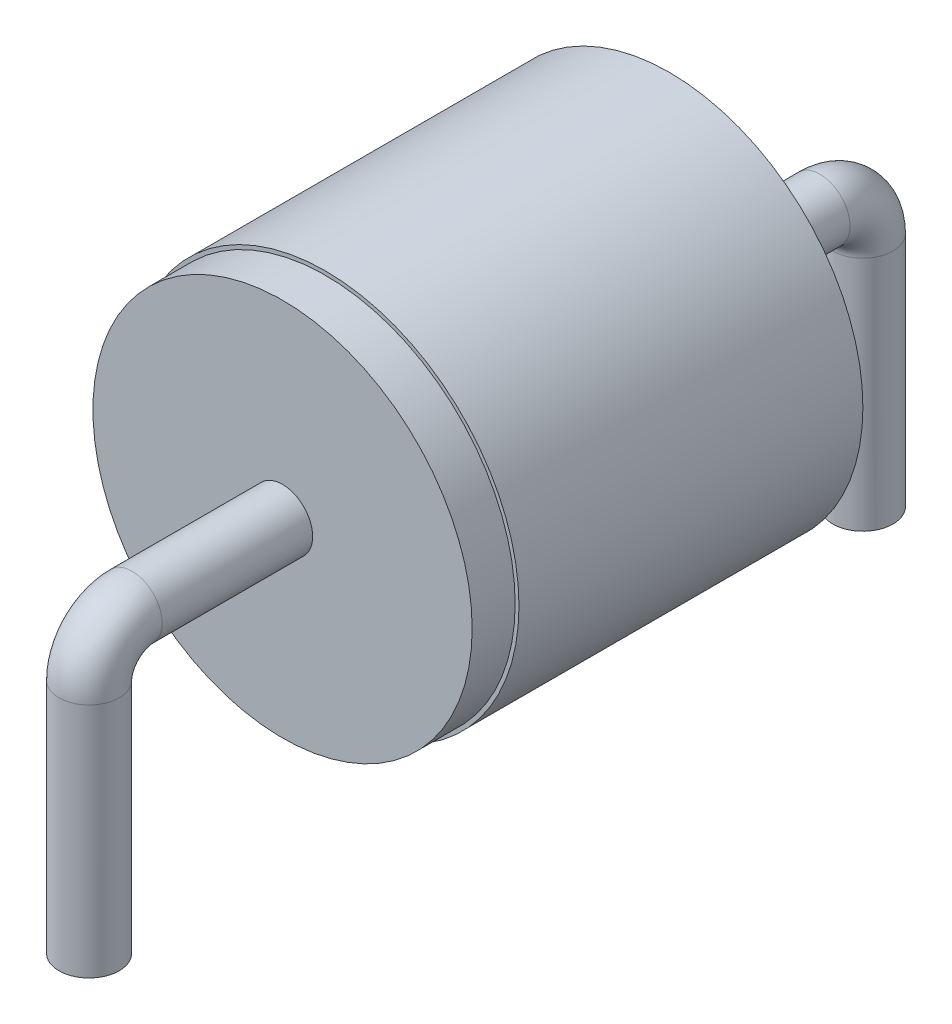
SolidWorks part; units mm, degrees
ref_plane "Спереди" through (0, 0, 0) normal (0, 0, 1) x (1, 0, 0)
ref_plane "Сверху" through (0, 0, 0) normal (0, 1, 0) x (1, 0, 0)
ref_plane "Справа" through (0, 0, 0) normal (1, 0, 0) x (0, 0, -1)
sketch "Эскиз1" plane through (0, 0, 0) normal (0, 0, 1) x (1, 0, 0)
  circle A0 centre (0, 0) radius 4.5
extrude "Бобышка-Вытянуть1" add sketch "Эскиз1" along normal mid plane 9
sketch "Эскиз2" plane through (0, 0, 4.5) normal (0, 0, 1) x (1, 0, 0)
  circle A0 centre (0, 0) radius 4.4109
  circle A1 centre (0, 0) radius 5.3334
extrude "Вырез-Вытянуть1" cut sketch "Эскиз2" against normal blind 1
sketch "Эскиз3" plane through (0, 0, 0) normal (1, 0, 0) x (0, 0, -1)
  line L0 (-8, 0) -> (8, 0)
  line L1 (9, -1) -> (9, -6.5)
  line L2 (0, 0) -> (0, -11.9524) construction
  line L3 (-9, -1) -> (-9, -6.5)
  line L4 (-3.5, -4.5) -> (4.5, -4.5) construction
  arc A0 (8, 0) -> (9, -1) centre (8, -1) cw
  arc A1 (-9, -1) -> (-8, 0) centre (-8, -1) cw
  point P12 (9, 0)
  point P15 (-9, 0)
  dimension "D3" = 1
  dimension "D1" = 9
  dimension "D2" = 2
sketch "Эскиз4" plane through (0, 0, 0) normal (0, 0, 1) x (1, 0, 0)
  circle A0 centre (0, 0) radius 0.7
sweep "По траектории1" add profiles "Эскиз4" path "Эскиз3"
